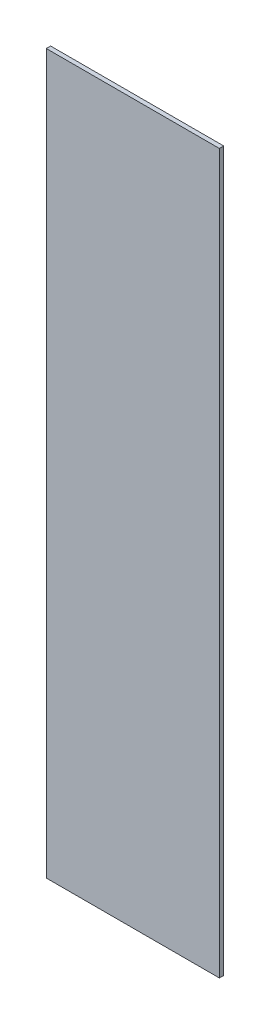
SolidWorks part; units mm, degrees
ref_plane "前视基准面" through (0, 0, 0) normal (0, 0, 1) x (1, 0, 0)
ref_plane "上视基准面" through (0, 0, 0) normal (0, 1, 0) x (1, 0, 0)
ref_plane "右视基准面" through (0, 0, 0) normal (1, 0, 0) x (0, 0, -1)
sketch "草图1" plane through (0, 0, 0) normal (0, 0, 1) x (1, 0, 0)
  line L1 (-10, -41.5) -> (10, -41.5)
  line L2 (-10, -41.5) -> (-10, 41.5)
  line L3 (-10, 41.5) -> (10, 41.5)
  line L4 (10, -41.5) -> (10, 41.5)
  line L5 (-10, -41.5) -> (10, 41.5) construction
  line L6 (-10, 41.5) -> (10, -41.5) construction
  point P0 (0, 0)
  dimension "D1" = 83
  dimension "D2" = 20
extrude "凸台-拉伸1" add sketch "草图1" along normal blind 0.5
